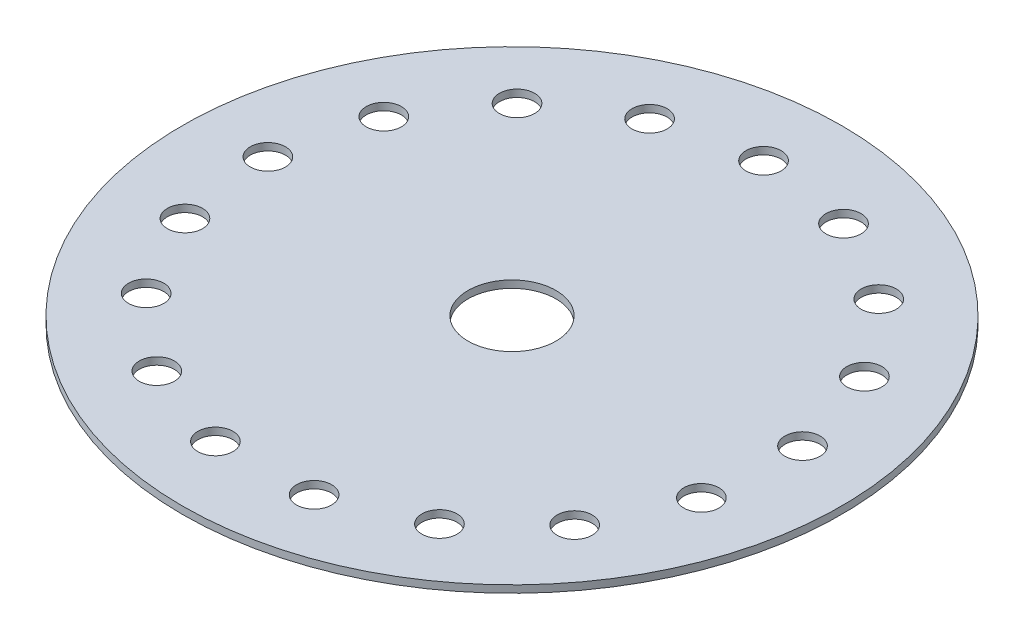
SolidWorks part; units mm, degrees
ref_plane "Спереди" through (0, 0, 0) normal (0, 0, 1) x (1, 0, 0)
ref_plane "Сверху" through (0, 0, 0) normal (0, 1, 0) x (1, 0, 0)
ref_plane "Справа" through (0, 0, 0) normal (1, 0, 0) x (0, 0, -1)
sketch "Эскиз1" plane through (0, 0, 0) normal (0, 1, 0) x (1, 0, 0)
  circle A0 centre (0, 0) radius 90
extrude "Вытянуть1" add sketch "Эскиз1" along normal blind 2
sketch "Эскиз2" plane through (0, 0, 0) normal (0, 1, 0) x (1, 0, 0)
  circle A0 centre (68.9251, -17.2089) radius 4.8
  circle A1 centre (58.0542, -40.9455) radius 4.8
  circle A2 centre (39.3427, -59.1521) radius 4.8
  circle A3 centre (15.3178, -69.3699) radius 4.8
  circle A4 centre (-10.7759, -70.2189) radius 4.8
  circle A5 centre (-35.4142, -61.5845) radius 4.8
  circle A6 centre (-55.2697, -44.6327) radius 4.8
  circle A7 centre (-67.6606, -21.6531) radius 4.8
  circle A8 centre (-70.9137, 4.251) radius 4.8
  circle A9 centre (-64.5894, 29.5809) radius 4.8
  circle A10 centre (-49.542, 50.9157) radius 4.8
  circle A11 centre (-27.8036, 65.3741) radius 4.8
  circle A12 centre (-2.3103, 71.0034) radius 4.8
  circle A13 centre (23.4951, 67.0433) radius 4.8
  circle A14 centre (46.1274, 54.0285) radius 4.8
  circle A15 centre (62.5299, 33.717) radius 4.8
  circle A16 centre (70.4873, 8.8518) radius 4.8
  circle A17 centre (0, 0) radius 12
extrude "Вырез-Вытянуть3" cut sketch "Эскиз2" along normal through all
